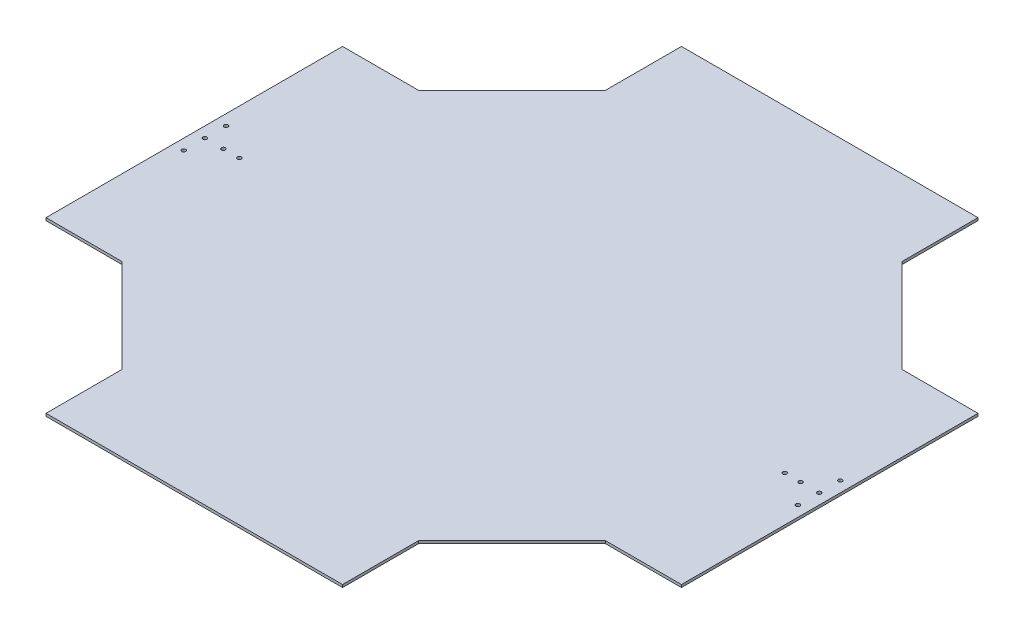
SolidWorks part; units mm, degrees
material "Acrylic (Medium-high impact)"
ref_plane "Front Plane" through (0, 0, 0) normal (0, 0, 1) x (1, 0, 0)
ref_plane "Top Plane" through (0, 0, 0) normal (0, 1, 0) x (1, 0, 0)
ref_plane "Right Plane" through (0, 0, 0) normal (1, 0, 0) x (0, 0, -1)
sketch "Sketch1" plane through (0, 0, 0) normal (0, 1, 0) x (1, 0, 0)
  line L0 (-381, 177.8) -> (-289.7187, 177.8)
  line L1 (-177.8, -381) -> (177.8, -381)
  line L2 (-381, -177.8) -> (-381, 177.8)
  line L3 (-177.8, 381) -> (177.8, 381)
  line L4 (381, -177.8) -> (381, 177.8)
  line L5 (0, 381) -> (0, -381) construction
  line L6 (-381, 0) -> (381, 0) construction
  line L7 (-289.7187, 177.8) -> (-177.8, 289.7188)
  line L8 (-177.8, 289.7188) -> (-177.8, 381)
  line L9 (177.8, 289.7188) -> (177.8, 381)
  line L10 (289.7187, 177.8) -> (177.8, 289.7188)
  line L11 (381, 177.8) -> (289.7187, 177.8)
  line L12 (-381, -177.8) -> (-289.7187, -177.8)
  line L13 (-177.8, -289.7188) -> (-177.8, -381)
  line L14 (381, -177.8) -> (289.7187, -177.8)
  line L15 (177.8, -289.7188) -> (177.8, -381)
  line L16 (289.7187, -177.8) -> (177.8, -289.7188)
  line L17 (-289.7187, -177.8) -> (-177.8, -289.7188)
  point P0 (0, 0)
  dimension "D1" = 762
  dimension "D2" = 135
  dimension "D3" = 203.2
  dimension "D4" = 91.2812
extrude "Boss-Extrude1" add sketch "Sketch1" along normal mid plane 3.175
sketch "Sketch2" plane through (0, 1.5875, 0) normal (0, 1, 0) x (1, 0, 0)
  line L0 (0, 0) -> (-50000, 0) construction
  line L1 (-368.3, -25.4) -> (-368.3, 25.4) construction
  line L2 (-381, 177.8) -> (-381, -177.8) construction
  line L3 (0, 0) -> (0, 50000) construction
  line L4 (368.3, -25.4) -> (368.3, 25.4) construction
  circle A0 centre (-346.075, 0) radius 2.3813
  circle A1 centre (-368.3, 0) radius 2.3813
  circle A2 centre (-368.3, 25.4) radius 2.3813
  circle A3 centre (-368.3, -25.4) radius 2.3813
  circle A4 centre (368.3, -25.4) radius 2.3813
  circle A5 centre (368.3, 25.4) radius 2.3813
  circle A6 centre (368.3, 0) radius 2.3813
  circle A7 centre (346.075, 0) radius 2.3813
  circle A8 centre (-327.025, 0) radius 2.3813
  circle A9 centre (327.025, 0) radius 2.3813
  point P15 (-368.3, 0)
  point P25 (368.3, 0)
  dimension "D1" = 4.7625
  dimension "D5" = 19.05
  dimension "D6" = 19.05
  dimension "D2" = 50.8
  dimension "D3" = 22.225
  dimension "D4" = 12.7
extrude "Cut-Extrude1" cut sketch "Sketch2" against normal through all
